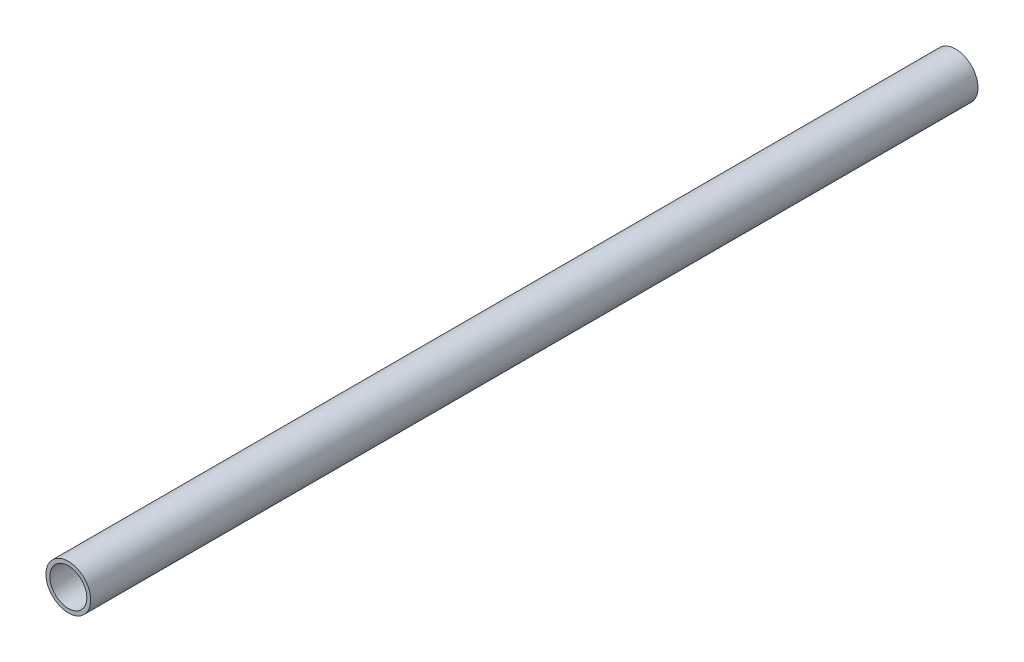
SolidWorks part; units mm, degrees
material "6061-T6 (SS)"
ref_plane "Front Plane" through (0, 0, 0) normal (0, 0, 1) x (1, 0, 0)
ref_plane "Top Plane" through (0, 0, 0) normal (0, 1, 0) x (1, 0, 0)
ref_plane "Right Plane" through (0, 0, 0) normal (1, 0, 0) x (0, 0, -1)
sketch "Sketch1" plane through (0, 0, 0) normal (0, 0, 1) x (1, 0, 0)
  line L0 (-9.525, 0) -> (9.525, 0) construction
  line L1 (0, -9.525) -> (0, 9.525) construction
  circle A0 centre (0, 0) radius 9.525
  circle A1 centre (0, 0) radius 7.874
  point P4 (0, 0)
  point P9 (0, 0)
  point P10 (7.874, 0)
  dimension "D1" = 15.748
  dimension "OD" = 19.05
  dimension "Wall Thickness" = 1.651
sketch "Sketch2" plane through (0, 0, 0) normal (1, 0, 0) x (0, 0, -1)
  line L0 (188.9125, 9.525) -> (-188.9125, 9.525) construction
  line L1 (0, 9.525) -> (0, -9.525) construction
  point P3 (-167.005, 9.525)
  point P4 (0, 9.525)
  point P5 (167.005, 9.525)
  dimension "D1" = 21.9075
  dimension "D2" = 21.9075
  dimension "Length" = 377.825
sketch "Sketch3" plane through (0, 0, 0) normal (0, 0, 1) x (1, 0, 0)
  line L0 (0, -9.525) -> (0, 9.525) construction
  circle A0 centre (0, 0) radius 9.525
  circle A1 centre (0, 0) radius 7.874
  circle A2 centre (0, 0) radius 7.874 construction
extrude "Boss-Extrude1" add sketch "Sketch3" along normal mid plane 377.825
equation "\"D1@Boss-Extrude1\" = \"Length@Sketch2\""
equation "\"D1@Sketch2\"=\"OD@Sketch1\"*1.15"
equation "\"D2@Sketch2\"=\"D1@Sketch2\""
